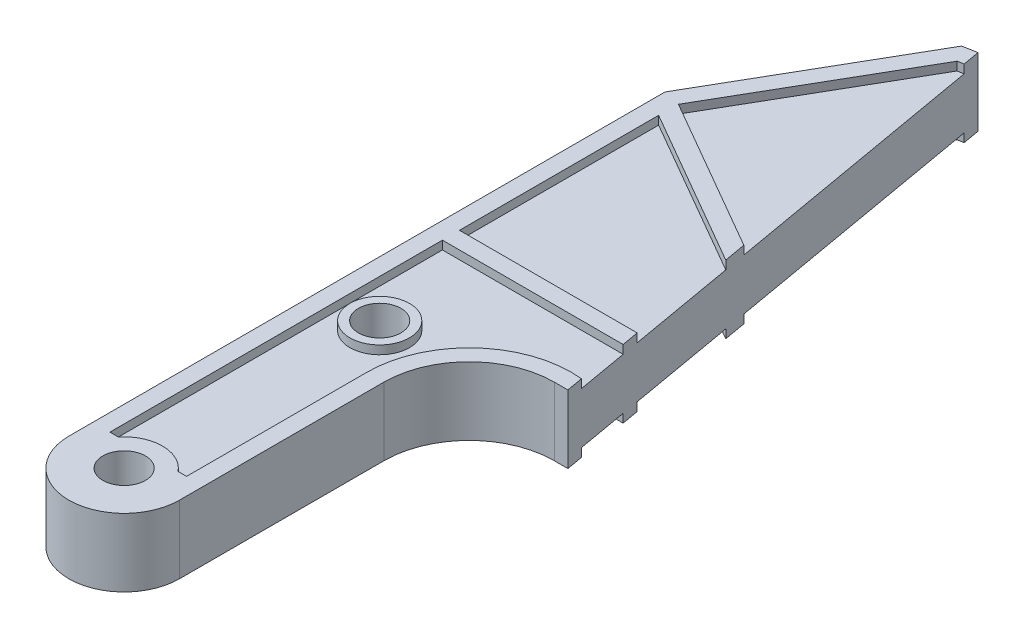
SolidWorks part; units mm, degrees
ref_plane "Alzado" through (0, 0, 0) normal (0, 0, 1) x (1, 0, 0)
ref_plane "Planta" through (0, 0, 0) normal (0, 1, 0) x (1, 0, 0)
ref_plane "Vista lateral" through (0, 0, 0) normal (1, 0, 0) x (0, 0, -1)
sketch "Croquis2" plane through (0, 0, 0) normal (0, 1, 0) x (1, 0, 0)
  line L0 (11.4519, 91.3762) -> (12.1465, 87.437) construction
  line L1 (9.8296, 89.0593) -> (11.7992, 89.4066) construction
  line L2 (12.1465, 87.437) -> (12.8411, 83.4977) construction
  line L3 (10.5241, 85.1201) -> (12.4938, 85.4673) construction
  line L4 (12.8411, 83.4977) -> (13.5357, 79.5585) construction
  line L5 (13.1884, 81.5281) -> (11.2187, 81.1808) construction
  line L6 (21.6213, 44.1213) -> (21.6213, 40.1213) construction
  line L7 (21.6213, 42.1213) -> (19.6213, 42.1213) construction
  line L8 (21.6213, 40.1213) -> (21.6213, 36.1213) construction
  line L9 (21.6213, 38.1213) -> (19.6213, 38.1213) construction
  line L36 (-6.5, 70) -> (-6.5, 0)
  line L37 (6.5, 0) -> (6.5, 24)
  line L38 (16.5, 34) -> (19.5, 34)
  line L39 (19.5, 34) -> (21.6213, 36.1213)
  line L40 (21.6213, 36.1213) -> (19.6213, 38.1213)
  line L41 (19.6213, 38.1213) -> (21.6213, 40.1213)
  line L42 (21.6213, 40.1213) -> (19.6213, 42.1213)
  line L43 (19.6213, 42.1213) -> (21.6213, 44.1213)
  line L45 (13.5357, 79.5585) -> (11.2187, 81.1808)
  line L46 (11.2187, 81.1808) -> (12.8411, 83.4977)
  line L47 (12.8411, 83.4977) -> (10.5241, 85.1201)
  line L48 (10.5241, 85.1201) -> (12.1465, 87.437)
  line L49 (12.1465, 87.437) -> (9.8296, 89.0593)
  line L50 (9.8296, 89.0593) -> (11.4519, 91.3762)
  line L51 (11.4519, 91.3762) -> (11.174, 92.9519)
  line L52 (11.174, 92.9519) -> (6.25, 92.0836)
  line L53 (6.25, 92.0836) -> (-6.5, 70)
  circle A0 centre (0, 0) radius 2.5
  circle A1 centre (0, 30) radius 2.5
  arc A11 (-6.5, 0) -> (6.5, 0) centre (0, 0) ccw
  arc A12 (16.5, 34) -> (6.5, 24) centre (16.5, 24) ccw
  arc A13 (13.5357, 79.5585) -> (21.6213, 44.1213) centre (106.5472, 82.1398) ccw
  dimension "D1" = 6.5
  dimension "D2" = 10
  dimension "D5" = 25.5
  dimension "D13" = 5
  dimension "D3" = 24
  dimension "D4" = 70
  dimension "D6" = 150
  dimension "D7" = 130
  dimension "D8" = 5
  dimension "D9" = 90
  dimension "D10" = 1.6
  dimension "D12" = 4
  dimension "D14" = 3
  dimension "D15" = 3
  dimension "D16" = 30
extrude "Saliente-Extruir1" add sketch "Croquis2" along normal blind 8
sketch "Croquis3" plane through (0, 8, 0) normal (0, 1, 0) x (1, 0, 0)
  line L0 (7.5157, 90.276) -> (-4.4602, 69.533)
  line L1 (-4.5, 67.2465) -> (-4.5, 43.8661)
  line L2 (-4.5, 43.8661) -> (18.2875, 43.8661)
  line L3 (8.5669, 90.4613) -> (12.8845, 65.9752)
  line L4 (-4.4602, 69.533) -> (14.4583, 58.6103)
  line L5 (-4.5, 67.2465) -> (15.2018, 55.8717)
  line L7 (-4.4602, 69.533) -> (10.5957, 60.8404) construction
  line L8 (-5.4602, 67.8009) -> (9.5957, 59.1083) construction
  line L55 (6.25, 92.0836) -> (-6.5, 70) construction
  line L56 (11.4519, 91.3762) -> (11.174, 92.9519) construction
  line L57 (7.5157, 90.276) -> (8.5669, 90.4613)
  line L58 (11.174, 92.9519) -> (6.25, 92.0836) construction
  line L59 (11.4519, 91.3762) -> (11.174, 92.9519) construction
  line L60 (-6.5, 70) -> (-6.5, 0) construction
  line L71 (-4.5, 2.8284) -> (-4.5, 41.8661)
  line L72 (-4.5, 41.8661) -> (18.2875, 41.8661)
  line L73 (18.2875, 41.8661) -> (18.2875, 35.8661)
  line L75 (18.2875, 43.8661) -> (18.2875, 46.8661)
  line L76 (4.5, 0) -> (4.5, 24)
  line L77 (4.5, 2.8284) -> (4.5, 24)
  line L78 (-4.5, 2.8284) -> (-3.5, 2.8284)
  line L79 (3.5, 2.8284) -> (4.5, 2.8284)
  arc A1 (15.2018, 55.8717) -> (18.2875, 46.8661) centre (106.5472, 82.1398) ccw
  circle A2 centre (0, 30) radius 3.5
  circle A3 centre (0, 30) radius 3.5
  arc A11 (11.5364, 79.503) -> (19.7959, 43.3041) centre (106.5472, 82.1398) ccw
  arc A12 (12.8845, 65.9752) -> (14.4583, 58.6103) centre (106.5472, 82.1398) ccw
  circle A22 centre (0, 0) radius 4.5
  arc A23 (3.5, 2.8284) -> (-3.5, 2.8284) centre (0, 0) ccw
  arc A26 (16.5, 36) -> (4.5, 24) centre (16.5, 24) ccw
  arc A27 (18.2875, 35.8661) -> (4.5, 24) centre (16.5, 24) ccw
  point P0 (11.313, 92.164)
  dimension "D2" = 2
  dimension "D3" = 2
  dimension "D4" = 3
  dimension "D5" = 2
  dimension "D8" = 2
  dimension "D9" = 6
  dimension "D10" = 3
  dimension "D11" = 1
  dimension "D14" = 23.3804
  dimension "D1" = 2
  dimension "D6" = 2
  dimension "D7" = 2
  dimension "D12" = 1
  dimension "D13" = 2
extrude "Cortar-Extruir1" cut sketch "Croquis3" against normal blind 1
sketch "Croquis4" plane through (0, 0, 0) normal (0, -1, 0) x (1, 0, 0)
  line L4 (14.4583, -58.6103) -> (-4.4602, -69.533)
  line L5 (-4.4602, -69.533) -> (7.5157, -90.276)
  line L6 (4.5, -24) -> (4.5, -2.8284)
  line L7 (18.2875, -41.8661) -> (18.2875, -35.8661)
  line L8 (-4.5, -41.8661) -> (18.2875, -41.8661)
  line L9 (-4.5, -2.8284) -> (-4.5, -41.8661)
  line L10 (-3.5, -2.8284) -> (-4.5, -2.8284)
  line L11 (4.5, -2.8284) -> (3.5, -2.8284)
  line L12 (4.5, -24) -> (4.5, -2.8284)
  line L13 (18.2875, -41.8661) -> (18.2875, -35.8661)
  line L14 (-4.5, -41.8661) -> (18.2875, -41.8661)
  line L15 (-4.5, -2.8284) -> (-4.5, -41.8661)
  line L16 (-3.5, -2.8284) -> (-4.5, -2.8284)
  line L17 (4.5, -2.8284) -> (3.5, -2.8284)
  line L18 (7.5157, -90.276) -> (8.5669, -90.4613)
  line L19 (8.5669, -90.4613) -> (12.8845, -65.9752)
  line L20 (14.4583, -58.6103) -> (-4.4602, -69.533)
  line L21 (-4.4602, -69.533) -> (7.5157, -90.276)
  line L22 (7.5157, -90.276) -> (8.5669, -90.4613)
  line L23 (8.5669, -90.4613) -> (12.8845, -65.9752)
  line L24 (-4.5, -67.2465) -> (15.2018, -55.8717)
  line L25 (18.2875, -46.8661) -> (18.2875, -43.8661)
  line L26 (18.2875, -43.8661) -> (-4.5, -43.8661)
  line L27 (-4.5, -43.8661) -> (-4.5, -67.2465)
  line L28 (-4.5, -67.2465) -> (15.2018, -55.8717)
  line L29 (18.2875, -46.8661) -> (18.2875, -43.8661)
  line L30 (18.2875, -43.8661) -> (-4.5, -43.8661)
  line L31 (-4.5, -43.8661) -> (-4.5, -67.2465)
  circle A2 centre (0, -30) radius 3.5
  circle A3 centre (0, -30) radius 3.5
  arc A4 (14.4583, -58.6103) -> (12.8845, -65.9752) centre (106.5472, -82.1398) ccw
  arc A5 (4.5, -24) -> (18.2875, -35.8661) centre (16.5, -24) ccw
  arc A6 (-3.5, -2.8284) -> (3.5, -2.8284) centre (0, 0) ccw
  arc A7 (4.5, -24) -> (18.2875, -35.8661) centre (16.5, -24) ccw
  arc A8 (-3.5, -2.8284) -> (3.5, -2.8284) centre (0, 0) ccw
  arc A9 (14.4583, -58.6103) -> (12.8845, -65.9752) centre (106.5472, -82.1398) ccw
  arc A10 (18.2875, -46.8661) -> (15.2018, -55.8717) centre (106.5472, -82.1398) ccw
  arc A11 (18.2875, -46.8661) -> (15.2018, -55.8717) centre (106.5472, -82.1398) ccw
  dimension "D1" = 0
  dimension "D2" = 0
  dimension "D3" = 0
  dimension "D4" = 0
extrude "Cortar-Extruir2" cut sketch "Croquis4" against normal blind 1
sketch "Sketch1" plane through (0, 0, 0) normal (0, -1, 0) x (-1, 0, 0)
  line L0 (-10.7257, 78.2183) -> (-13.5357, 79.5585)
  line L1 (-8.5669, 90.4613) -> (-12.8845, 65.9752) construction
  line L2 (-13.5357, 79.5585) -> (-11.2187, 81.1808)
  line L3 (-11.2187, 81.1808) -> (-12.8411, 83.4977)
  line L4 (-12.8411, 83.4977) -> (-10.5241, 85.1201)
  line L5 (-10.5241, 85.1201) -> (-12.1465, 87.437)
  line L6 (-12.1465, 87.437) -> (-9.8296, 89.0593)
  line L7 (-9.8296, 89.0593) -> (-11.4519, 91.3762)
  line L8 (-11.4519, 91.3762) -> (-11.174, 92.9519)
  line L9 (-11.174, 92.9519) -> (-8.712, 92.5178)
  line L10 (-11.174, 92.9519) -> (-6.25, 92.0836) construction
  line L11 (-8.712, 92.5178) -> (-10.7257, 78.2183)
extrude "Boss-Extrude1" add sketch "Sketch1" along normal blind 10 and the other way blind 18
sketch "Sketch2" plane through (0, 0, 0) normal (0, -1, 0) x (1, 0, 0)
  line L0 (20.8547, -45.8823) -> (20.0616, -46.6754)
  line L1 (20.0616, -46.6754) -> (20.0616, -47.8171)
  line L2 (20.0616, -47.8171) -> (19.0208, -48.8578)
  line L3 (19.0208, -48.8578) -> (19.2134, -50.0366)
  line L4 (19.2134, -50.0366) -> (18.3452, -50.9047)
  line L5 (18.3452, -50.9047) -> (18.6351, -51.6559)
  line L6 (18.6351, -51.6559) -> (18.3452, -51.6559)
  line L7 (18.3452, -52.505) -> (17.4753, -52.8407)
  line L8 (17.4753, -52.8407) -> (17.9422, -53.7326)
  line L9 (17.9422, -53.7326) -> (17.4753, -53.7326)
  line L10 (17.4753, -53.7326) -> (17.7319, -54.3973)
  line L11 (17.7319, -54.3973) -> (17.0603, -55.0689)
  line L12 (17.0603, -55.0689) -> (17.3336, -55.7059)
  line L13 (17.3336, -55.7059) -> (17.0603, -55.7059)
  line L14 (17.0603, -56.6466) -> (16.6318, -57.1592)
  line L15 (16.6318, -57.1592) -> (16.6318, -58.2015)
  line L16 (16.6318, -58.2015) -> (15.8313, -59.1594)
  line L17 (15.8313, -59.1594) -> (16.2336, -59.7508)
  line L18 (16.2336, -59.7508) -> (15.3634, -60.3428)
  line L19 (15.3634, -60.3428) -> (15.8313, -61.4413)
  line L20 (15.8313, -61.4413) -> (15.015, -61.9966)
  line L21 (15.015, -61.9966) -> (15.474, -63.0743)
  line L22 (15.474, -63.0743) -> (14.5946, -63.6726)
  line L23 (14.5946, -63.6726) -> (15.1807, -64.534)
  line L24 (15.1807, -64.534) -> (14.3403, -65.1057)
  line L25 (14.3403, -65.1057) -> (14.8554, -66.3151)
  line L26 (14.8554, -66.3151) -> (13.9154, -66.9546)
  line L27 (13.9154, -66.9546) -> (14.589, -67.9447)
  line L28 (14.589, -67.9447) -> (13.9154, -68.403)
  line L29 (13.9154, -68.403) -> (14.3673, -69.4639)
  line L30 (14.3673, -69.4639) -> (13.491, -70.0601)
  line L31 (13.491, -70.0601) -> (14.1633, -71.0483)
  line L32 (14.1633, -71.0483) -> (13.2683, -72.1192)
  line L33 (13.2683, -72.1192) -> (13.9786, -72.7128)
  line L34 (13.9786, -72.7128) -> (13.2683, -73.5627)
  line L35 (13.2683, -73.5627) -> (13.824, -74.3795)
  line L36 (13.824, -74.3795) -> (13.2683, -74.7576)
  line L37 (13.2683, -74.7576) -> (13.7405, -75.4517)
  line L38 (13.7405, -75.4517) -> (12.8022, -76.0901)
  line L39 (12.8022, -76.0901) -> (13.6258, -77.3005)
  line L40 (13.6258, -77.3005) -> (12.8022, -77.8608)
  line L41 (12.8022, -77.8608) -> (13.554, -78.9658)
  line L42 (13.554, -78.9658) -> (20.8547, -45.8823)
  line L43 (17.0603, -55.7059) -> (17.0603, -56.6466)
  line L44 (18.3452, -51.6559) -> (18.3452, -52.505)
  arc A0 (21.6213, -44.1213) -> (13.5357, -79.5585) centre (106.5472, -82.1398) ccw construction
extrude "Cut-Extrude1" cut sketch "Sketch2" against normal blind 10
sketch "Sketch3" plane through (0, 1, 0) normal (0, -1, 0) x (-1, 0, 0)
  line L0 (-19.6187, 25.2858) -> (-7.0413, 97.1241)
  line L1 (-7.0413, 97.1241) -> (-21.4083, 99.6394)
  line L2 (-19.6187, 25.2858) -> (-35.7965, 28.1182)
  line L3 (-35.7965, 28.1182) -> (-21.4083, 99.6394)
extrude "Cut-Extrude2" cut sketch "Sketch3" against normal blind 31 and the other way blind 46
